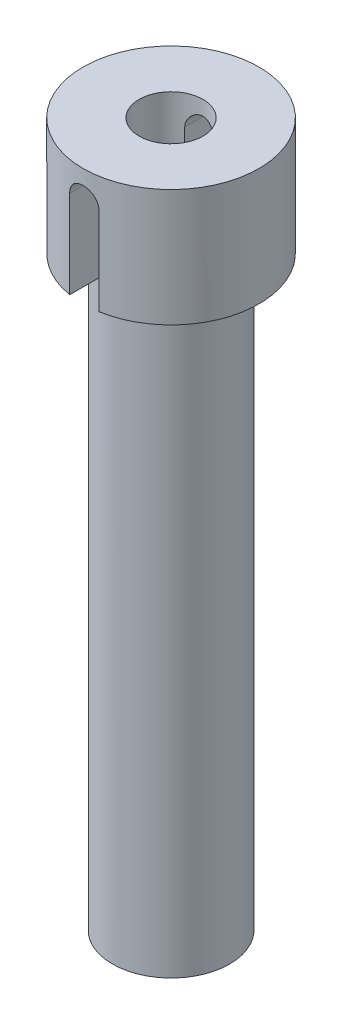
SolidWorks part; units mm, degrees
ref_plane "Front Plane" through (0, 0, 0) normal (0, 0, 1) x (1, 0, 0)
ref_plane "Top Plane" through (0, 0, 0) normal (0, 1, 0) x (1, 0, 0)
ref_plane "Right Plane" through (0, 0, 0) normal (1, 0, 0) x (0, 0, -1)
sketch "Sketch1" plane through (0, 0, 0) normal (0, 1, 0) x (1, 0, 0)
  circle A0 centre (0, 0) radius 3.175
  dimension "D1" = 6.35
extrude "Boss-Extrude1" add sketch "Sketch1" along normal blind 31.75
cosmetic thread "Cosmetic Thread2" parameters "D1"=12.7, "D2"=5.268
sketch "Sketch4" plane through (0, 31.75, 0) normal (0, 1, 0) x (1, 0, 0)
  circle A0 centre (0, 0) radius 4.7625
  dimension "D1" = 9.525
extrude "Boss-Extrude2" add sketch "Sketch4" along normal blind 6.35
hole_wizard "Tap Drill for #8-32 Tap2" positions "Sketch6" profile "Sketch5" hole size "#8-32" standard "ANSI Inch" end condition through all
sketch "Sketch6" plane through (0, 38.1, 0) normal (0, 1, 0) x (1, 0, 0)
  point P0 (0, 0)
sketch "Sketch5" plane through (0, 38.1, 0) normal (1, 0, 0) x (0, 0, 1)
  line L0 (0, 0) -> (0, 38.1)
  line L1 (0, 38.1) -> (1.7272, 38.1)
  line L2 (1.7272, 38.1) -> (1.7272, 0)
  line L5 (1.7272, 0) -> (0, 0)
  line L11 (0, -6.35) -> (0, 107.95) construction
  dimension "Thru Hole Dia." = 3.4544
  dimension "Thru Hole Depth" = 38.1
cosmetic thread "Cosmetic Thread3" parameters "D1"=12.7, "D2"=4.1656
sketch "Sketch8" plane through (0, 0, 0) normal (0, 0, 1) x (1, 0, 0)
  line L0 (0, 36.5125) -> (0, 31.75) construction
  line L1 (0.7937, 36.5125) -> (0.7938, 31.75)
  line L2 (-0.7937, 36.5125) -> (-0.7937, 31.75)
  line L3 (1.7272, 38.1) -> (-1.7272, 38.1) construction
  line L4 (-3.175, 31.75) -> (3.175, 31.75) construction
  arc A0 (0.7937, 36.5125) -> (-0.7937, 36.5125) centre (0, 36.5125) ccw
  arc A1 (-0.7937, 31.75) -> (0.7938, 31.75) centre (0, 31.75) ccw
  point P3 (0, 34.1313)
  dimension "D1" = 1.5875
  dimension "D2" = 1.5875
extrude "Cut-Extrude2" cut sketch "Sketch8" against normal through all both and the other way through all
